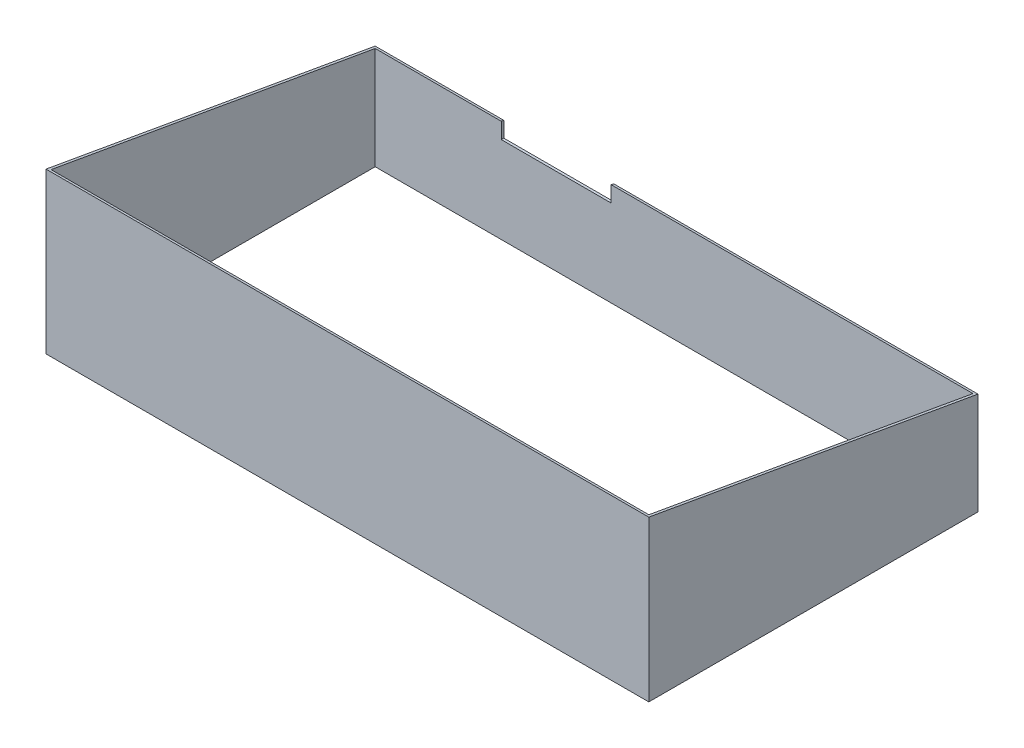
SolidWorks part; units mm, degrees
material "Particle Board"
ref_plane "Front Plane" through (0, 0, 0) normal (0, 0, 1) x (1, 0, 0)
ref_plane "Top Plane" through (0, 0, 0) normal (0, 1, 0) x (1, 0, 0)
ref_plane "Right Plane" through (0, 0, 0) normal (1, 0, 0) x (0, 0, -1)
sketch "Sketch1" plane through (0, 0, 0) normal (1, 0, 0) x (0, 0, -1)
  line L0 (0, 403.2291) -> (0, 0)
  line L1 (0, 0) -> (829.3066, 0)
  line L4 (829.3066, 0) -> (829.3066, 257)
  line L5 (0, 403.2291) -> (829.3066, 257)
  dimension "D1" = 10
  dimension "D2" = 842.1
  dimension "D3" = 257
extrude "Boss-Extrude1" add sketch "Sketch1" along normal blind 1518.68
shell "Shell1" thickness 6.35
sketch "Sketch3" plane through (0, 0, -822.9566) normal (0, 0, 1) x (1, 0, 0)
  line L0 (6.35, 0) -> (6.35, 258.1197) construction
  line L1 (324, 268.1197) -> (601, 268.1197)
  line L2 (324, 268.1197) -> (324, 218.1197)
  line L3 (324, 218.1197) -> (601, 218.1197)
  line L4 (601, 268.1197) -> (601, 218.1197)
  line L5 (1512.33, 258.1197) -> (6.35, 258.1197) construction
  dimension "D1" = 317.65
  dimension "D2" = 277
  dimension "D3" = 10
  dimension "D4" = 40
extrude "Cut-Extrude2" cut sketch "Sketch3" against normal up to next
